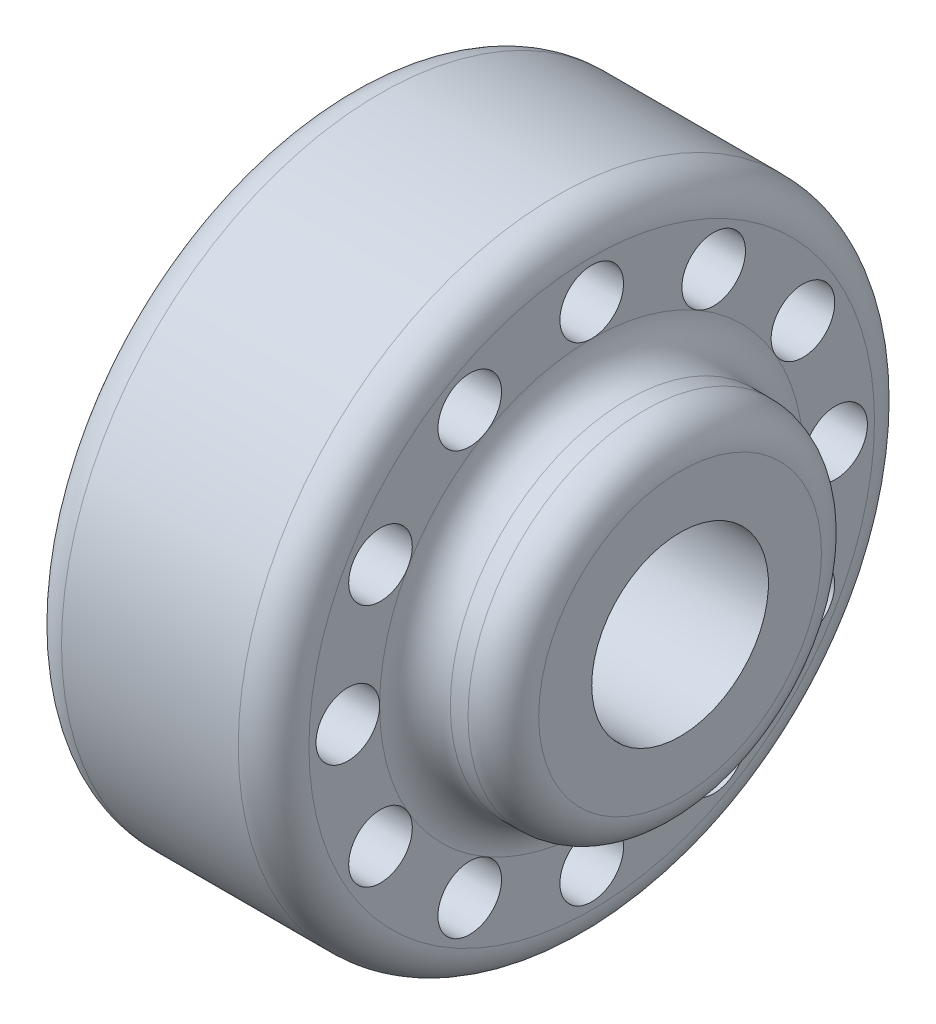
SolidWorks part; units mm, degrees
ref_plane "Front Plane" through (0, 0, 0) normal (0, 0, 1) x (1, 0, 0)
ref_plane "Top Plane" through (0, 0, 0) normal (0, 1, 0) x (1, 0, 0)
ref_plane "Right Plane" through (0, 0, 0) normal (1, 0, 0) x (0, 0, -1)
sketch "Sketch1" plane through (0, 0, 0) normal (0, 0, 1) x (1, 0, 0)
  line L0 (0, 0) -> (79.0192, 0) construction
  line L1 (-22.5, 25) -> (-25, 25)
  line L2 (30, 12.5) -> (-30, 12.5)
  line L3 (30, 12.5) -> (30, 20)
  line L4 (25, 25) -> (22.5, 25)
  line L5 (-30, 12.5) -> (-30, 20)
  line L7 (-17.5, 30) -> (-17.5, 40)
  line L8 (-12.5, 45) -> (12.5, 45)
  line L9 (17.5, 30) -> (17.5, 40)
  line L10 (0, 0) -> (0, 45) construction
  arc A0 (25, 25) -> (30, 20) centre (25, 20) cw
  arc A1 (22.5, 25) -> (17.5, 30) centre (22.5, 30) cw
  arc A2 (12.5, 45) -> (17.5, 40) centre (12.5, 40) cw
  arc A3 (-12.5, 45) -> (-17.5, 40) centre (-12.5, 40) ccw
  arc A4 (-22.5, 25) -> (-17.5, 30) centre (-22.5, 30) ccw
  arc A5 (-25, 25) -> (-30, 20) centre (-25, 20) ccw
  point P2 (0, 0)
  point P18 (17.5, 45)
  point P21 (-17.5, 45)
  point P24 (-17.5, 25)
  point P27 (0, 0)
  point P28 (0, 0)
  point P29 (0, 0)
  point P31 (0, 0)
  point P32 (0, 0)
  point P33 (0, 0)
  dimension "D5" = 5
  dimension "D1" = 35
  dimension "D2" = 60
  dimension "D3" = 50
  dimension "D4" = 90
  dimension "D6" = 25
revolve "Revolve1" add sketch "Sketch1" angle 360 about L0
sketch "Sketch2" plane through (17.5, 0, 0) normal (1, 0, 0) x (0, 0, -1)
  circle A0 centre (0, 34.5) radius 4.5
  point P2 (0, 0)
  point P4 (0, 33.972)
  point P5 (0, 0)
  point P6 (0, 0)
  point P7 (0, 0)
  point P8 (0, 0)
  point P9 (0, 0)
  point P10 (0, 0)
  dimension "D2" = 9
  dimension "D1" = 34.5
extrude "Cut-Extrude1" cut sketch "Sketch2" against normal up to surface (35 mm away) up to face at (-17.5, 0, 30)
pattern_circular "CirPattern1" count 12 over 360 about axis through (0, 0, 0) along (1, 0, 0) of "Cut-Extrude1"
